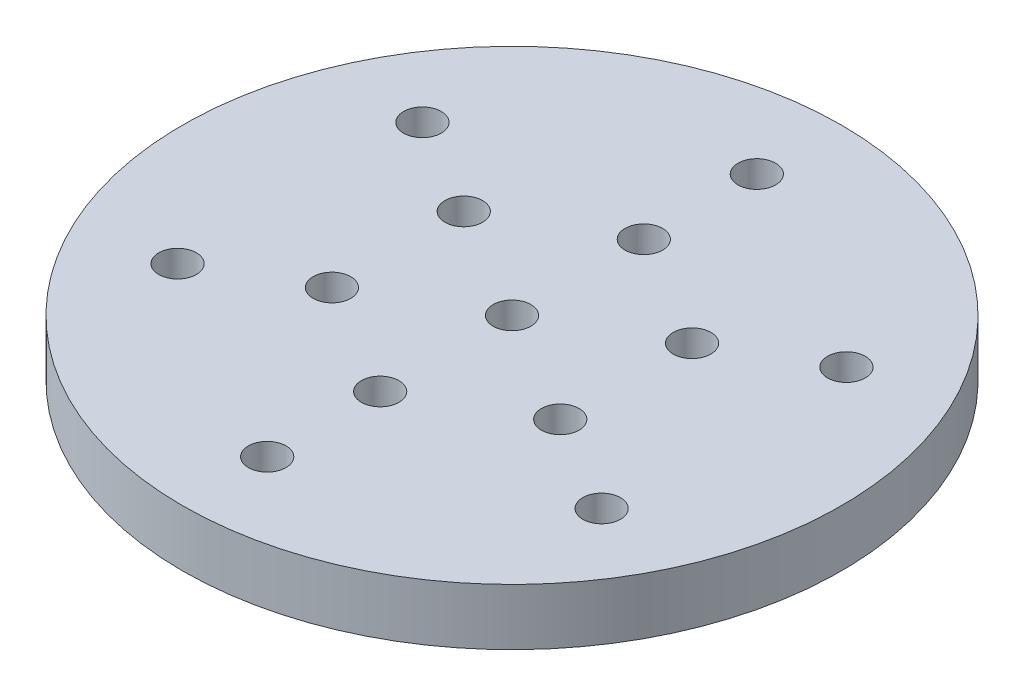
SolidWorks part; units mm, degrees
ref_plane "Front Plane" through (0, 0, 0) normal (0, 0, 1) x (1, 0, 0)
ref_plane "Top Plane" through (0, 0, 0) normal (0, 1, 0) x (1, 0, 0)
ref_plane "Right Plane" through (0, 0, 0) normal (1, 0, 0) x (0, 0, -1)
sketch "Sketch2" plane through (0, 0, 0) normal (0, 1, 0) x (1, 0, 0)
  circle A0 centre (0, 0) radius 17.5
  circle A1 centre (0, 13) radius 1
  circle A9 centre (0, 7) radius 1
  circle A14 centre (11.2583, 6.5) radius 1
  circle A15 centre (11.2583, -6.5) radius 1
  circle A16 centre (0, -13) radius 1
  circle A17 centre (-11.2583, -6.5) radius 1
  circle A18 centre (-11.2583, 6.5) radius 1
  circle A20 centre (0, 0) radius 1
  circle A21 centre (6.0622, 3.5) radius 1
  circle A22 centre (6.0622, -3.5) radius 1
  circle A23 centre (0, -7) radius 1
  circle A24 centre (-6.0622, -3.5) radius 1
  circle A25 centre (-6.0622, 3.5) radius 1
  point P6 (0, 0)
  point P14 (0, 0)
  point P19 (0, 0)
  point P23 (0, 0)
  point P32 (0, 0)
  point P35 (0, 0)
  dimension "D1" = 35
  dimension "D2" = 2
  dimension "D5" = 6
  dimension "D9" = 6
  dimension "D3" = 13
  dimension "D6" = 13
  dimension "D7" = 6
  dimension "D4" = 6
extrude "Boss-Extrude1" add sketch "Sketch2" along normal blind 3
